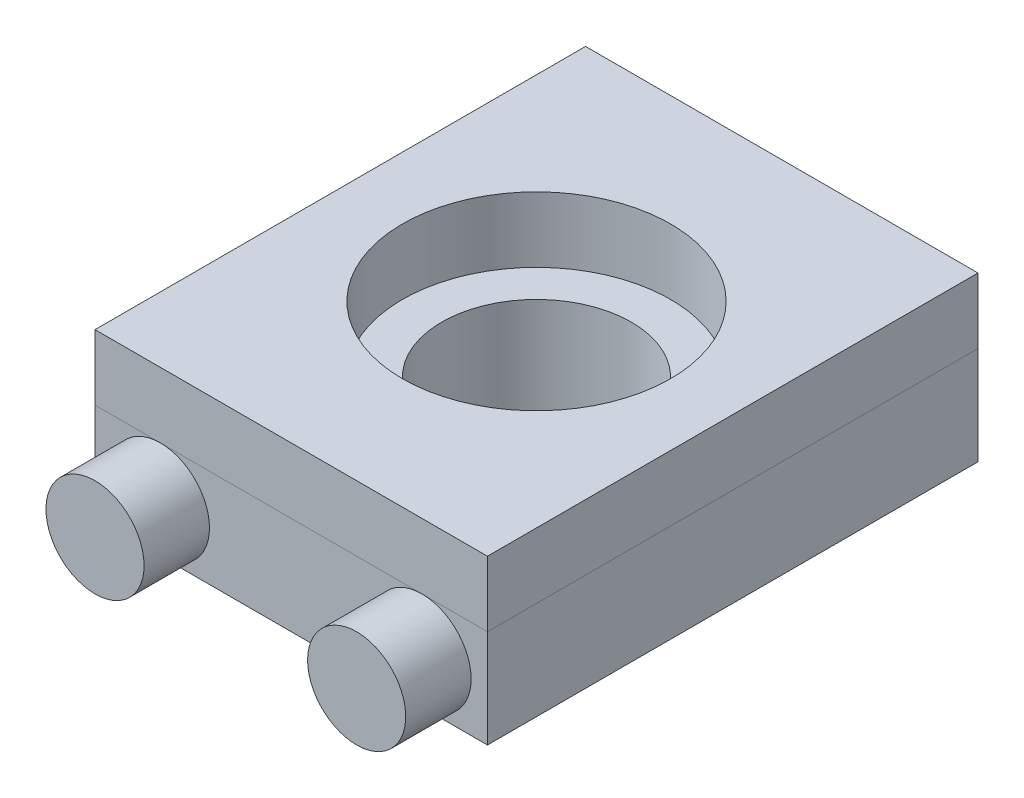
SolidWorks part; units mm, degrees
ref_plane "前视基准面" through (0, 0, 0) normal (0, 0, 1) x (1, 0, 0)
ref_plane "上视基准面" through (0, 0, 0) normal (0, 1, 0) x (1, 0, 0)
ref_plane "右视基准面" through (0, 0, 0) normal (1, 0, 0) x (0, 0, -1)
other "Configuration Table"
sketch "草图1" plane through (0, 0, 0) normal (0, 1, 0) x (1, 0, 0)
  line L0 (6, 15) -> (6, 0) construction
  line L1 (0, 0) -> (12, 0)
  line L2 (0, 0) -> (0, 15)
  line L3 (0, 15) -> (12, 15)
  line L4 (12, 0) -> (12, 15)
  circle A0 centre (6, 7.5) radius 2.9
  circle A1 centre (6, 7.5) radius 4.1
  dimension "D3" = 5.8
  dimension "D4" = 8.2
  dimension "D1" = 12
  dimension "D2" = 15
  dimension "D5" = 7.5
extrude "凸台-拉伸1" add sketch "草图1" along normal blind 3 contours L2 L1 L4 L3 | A0
sketch "草图3" plane through (0, 3, 0) normal (0, 1, 0) x (1, 0, 0)
  line L1 (0, 15) -> (12, 15)
  line L2 (0, 15) -> (0, 0)
  line L3 (0, 0) -> (12, 0)
  line L4 (12, 15) -> (12, 0)
  circle A0 centre (6, 7.5) radius 4.1
  circle A1 centre (6, 7.5) radius 2.9 construction
  circle A2 centre (6, 7.5) radius 2.9
  line M6 (12, 15) -> (0, 15)
  line M7 (0, 15) -> (0, 0)
  line M8 (0, 0) -> (12, 0)
  line M9 (12, 0) -> (12, 15)
  dimension "D1" = 8.2
extrude "凸台-拉伸2" add sketch "草图3" along normal blind 2 contours A0 M9 M6 M7 M8
sketch "草图7" plane through (0, 0, 0) normal (0, 0, 1) x (1, 0, 0)
  line L0 (12, 1.5) -> (0, 1.5) construction
  line L1 (12, 3) -> (12, 0) construction
  line L2 (0, 3) -> (0, 0) construction
  line L3 (6, 5) -> (6, 0) construction
  line L4 (0, 5) -> (12, 5) construction
  line L5 (0, 0) -> (12, 0) construction
  line L6 (0, 5) -> (0, 3) construction
  circle A0 centre (2, 1.5) radius 1.5
  circle A2 centre (10, 1.5) radius 1.5
  dimension "D1" = 3
  dimension "D2" = 4
  dimension "D3" = 2
extrude "凸台-拉伸3" add sketch "草图7" along normal blind 2
